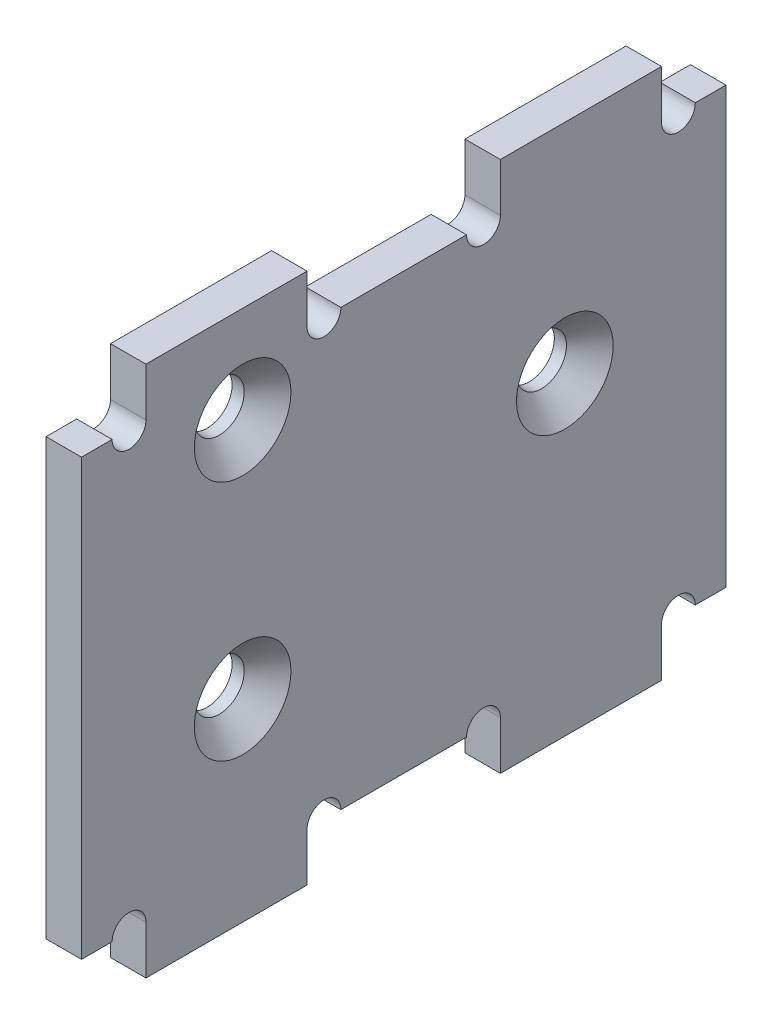
SolidWorks part; units mm, degrees
material "Thornel Mat VMA"
ref_plane "前视基准面" through (0, 0, 0) normal (0, 0, 1) x (1, 0, 0)
ref_plane "上视基准面" through (0, 0, 0) normal (0, 1, 0) x (1, 0, 0)
ref_plane "右视基准面" through (0, 0, 0) normal (1, 0, 0) x (0, 0, -1)
sketch "草图1" plane through (0, 0, 0) normal (1, 0, 0) x (0, 0, -1)
  line L0 (-16, 13.5) -> (-16, 16.5)
  line L1 (15, -5) -> (-15, -5) construction
  line L2 (15, -5) -> (15, 5) construction
  line L3 (15, 5) -> (-15, 5) construction
  line L4 (-15, -5) -> (-15, 5) construction
  line L5 (15, -5) -> (-15, 5) construction
  line L6 (15, 5) -> (-15, -5) construction
  line L7 (20, -13.5) -> (16, -13.5)
  line L8 (20, -13.5) -> (20, 13.5)
  line L9 (20, 13.5) -> (16, 13.5)
  line L10 (-20, -13.5) -> (-20, 13.5)
  line L11 (20, -13.5) -> (-20, 13.5) construction
  line L12 (20, 13.5) -> (-20, -13.5) construction
  line L13 (-16, 16.5) -> (-6, 16.5)
  line L14 (-6, 16.5) -> (-6, 13.5)
  line L15 (-11, 16.5) -> (-11, 8.3937) construction
  line L16 (-16, 13.5) -> (-20, 13.5)
  line L17 (0, 0) -> (0, 8.3937) construction
  line L18 (6, 16.5) -> (6, 13.5)
  line L19 (16, 16.5) -> (6, 16.5)
  line L20 (16, 13.5) -> (16, 16.5)
  line L21 (6, 13.5) -> (-6, 13.5)
  line L22 (0, 0) -> (13.4997, 0) construction
  line L23 (16, -13.5) -> (16, -16.5)
  line L24 (16, -16.5) -> (6, -16.5)
  line L25 (6, -16.5) -> (6, -13.5)
  line L26 (-6, -16.5) -> (-6, -13.5)
  line L27 (-16, -16.5) -> (-6, -16.5)
  line L28 (-16, -13.5) -> (-16, -16.5)
  line L29 (-16, -13.5) -> (-20, -13.5)
  line L30 (6, -13.5) -> (-6, -13.5)
  line L36 (11, 16.5) -> (11, 10.3214) construction
  line L37 (10, 3) -> (-11.9632, 3) construction
  circle A4 centre (-17.05, 13.5) radius 1.05
  circle A5 centre (-4.95, 13.5) radius 1.05
  circle A6 centre (17.05, 13.5) radius 1.05
  circle A7 centre (4.95, 13.5) radius 1.05
  circle A8 centre (17.05, -13.5) radius 1.05
  circle A9 centre (4.95, -13.5) radius 1.05
  circle A10 centre (-4.95, -13.5) radius 1.05
  circle A11 centre (-17.05, -13.5) radius 1.05
  circle A13 centre (-10, 10.5) radius 1.55
  circle A16 centre (10, 3) radius 1.55
  circle A17 centre (-10, -4.5) radius 1.55
  point P0 (0, 0)
  point P10 (0, 0)
  dimension "D8" = 2.1
  dimension "D12" = 1
  dimension "D11" = 10.5
  dimension "D13" = 3.1
  dimension "D14" = 20
  dimension "D2" = 22
  dimension "D3" = 10
  dimension "D4" = 27
  dimension "D5" = 5
  dimension "D6" = 10
  dimension "D7" = 9
  dimension "D9" = 3
  dimension "D10" = 7.5
  dimension "D15" = 3
extrude "凸台-拉伸1" add sketch "草图1" along normal blind 2.2
hole_wizard "打孔尺寸(%根据十字)槽沉头木螺钉的类型1" positions "3D草图1" profile "草图2" countersink size "M3" standard "GB" end condition through all
sketch3d "3D草图1"
  line L0 (2.2, 10.5, 10) -> (0, 10.5, 10) construction
  line L1 (2.2, 3, -10) -> (0, 3, -10) construction
  line L2 (2.2, -4.5, 10) -> (0, -4.5, 10) construction
  point P0 (2.2, 10.5, 10)
  point P4 (2.2, 3, -10)
  point P8 (2.2, -4.5, 10)
sketch "草图2" plane through (2.2, 10.5, 10) normal (0, 1, 0) x (0, 0, -1)
  line L0 (0, 0) -> (0, 2.2)
  line L1 (0, 2.2) -> (1.55, 2.2)
  line L2 (1.55, 2.2) -> (1.55, 1.45)
  line L3 (1.55, 1.45) -> (3, 0)
  line L5 (3, 0) -> (0, 0)
  line L6 (-1.55, 1.45) -> (-3, 0) construction
  line L11 (0, -6.35) -> (0, 107.95) construction
  dimension "通孔孔直径" = 3.1
  dimension "通孔孔深度" = 2.2
  dimension "近端锥形沉头孔直径" = 6
  dimension "近端锥形沉头孔角度" = 90
